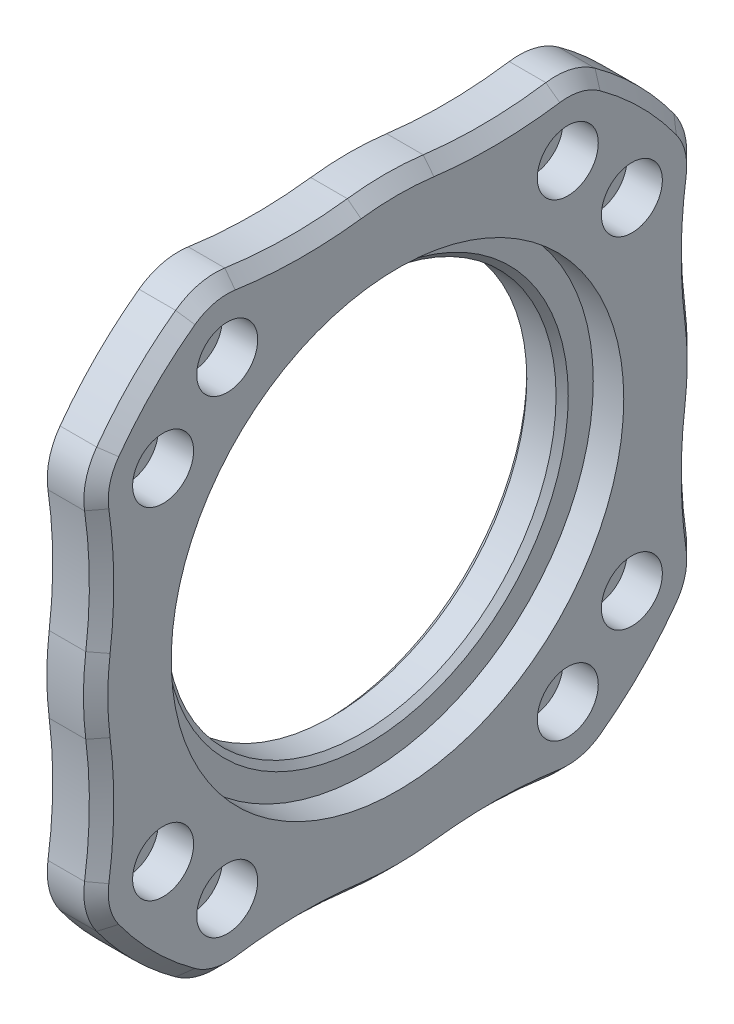
SolidWorks part; units mm, degrees
ref_plane "前视基准面" through (0, 0, 0) normal (1, 0, 0) x (0, 1, 0)
ref_plane "上视基准面" through (0, 0, 0) normal (0, 0, 1) x (0, 1, 0)
ref_plane "右视基准面" through (0, 0, 0) normal (0, 1, 0) x (-1, 0, 0)
other "Configuration Table"
sketch "草图1" plane through (0, 0, 0) normal (1, 0, 0) x (0, 1, 0)
  circle A0 centre (0, 0) radius 30
  dimension "D1" = 60
extrude "凸台-拉伸1" add sketch "草图1" along normal blind 4
sketch "草图2" plane through (0, 0, 0) normal (-1, 0, 0) x (0, -1, 0)
  line L0 (0, 30) -> (0, 0) construction
  line L1 (0, 0) -> (-30, 0) construction
  line L3 (-13.9599, -19.2142) -> (0, 0) construction
  line L4 (0, 0) -> (-21.2132, -21.2132) construction
  arc A0 (-15.4294, -21.2367) -> (-13.5954, -21.6874) centre (-13.9599, -19.2142) ccw
  arc A1 (-2.7345, -21.5774) -> (-13.5954, -21.6874) centre (-7.7635, -61.26) ccw
  arc A2 (-2.7345, -21.5774) -> (2.7345, -21.5774) centre (0, 0) ccw
  arc A3 (-21.2367, -15.4294) -> (-15.4294, -21.2367) centre (0, 0) ccw
  arc A4 (-21.2367, -15.4294) -> (-21.6874, -13.5954) centre (-19.2142, -13.9599) cw
  arc A5 (-21.5774, -2.7345) -> (-21.6874, -13.5954) centre (-61.26, -7.7635) cw
  arc A6 (-21.5774, -2.7345) -> (-21.5774, 2.7345) centre (0, 0) cw
  arc A7 (-21.5774, 2.7345) -> (-21.6874, 13.5954) centre (-61.26, 7.7635) ccw
  arc A8 (-21.2367, 15.4294) -> (-21.6874, 13.5954) centre (-19.2142, 13.9599) ccw
  arc A9 (-21.2367, 15.4294) -> (-15.4294, 21.2367) centre (0, 0) cw
  arc A10 (-15.4294, 21.2367) -> (-13.5954, 21.6874) centre (-13.9599, 19.2142) cw
  arc A11 (-2.7345, 21.5774) -> (-13.5954, 21.6874) centre (-7.7635, 61.26) cw
  arc A12 (-2.7345, 21.5774) -> (2.7345, 21.5774) centre (0, 0) cw
  arc A13 (15.4294, 21.2367) -> (13.5954, 21.6874) centre (13.9599, 19.2142) ccw
  arc A14 (2.7345, 21.5774) -> (13.5954, 21.6874) centre (7.7635, 61.26) ccw
  arc A15 (21.2367, 15.4294) -> (15.4294, 21.2367) centre (0, 0) ccw
  arc A16 (21.2367, 15.4294) -> (21.6874, 13.5954) centre (19.2142, 13.9599) cw
  arc A17 (21.5774, 2.7345) -> (21.6874, 13.5954) centre (61.26, 7.7635) cw
  arc A18 (21.5774, -2.7345) -> (21.5774, 2.7345) centre (0, 0) ccw
  arc A19 (21.5774, -2.7345) -> (21.6874, -13.5954) centre (61.26, -7.7635) ccw
  arc A20 (21.2367, -15.4294) -> (21.6874, -13.5954) centre (19.2142, -13.9599) ccw
  arc A21 (21.2367, -15.4294) -> (15.4294, -21.2367) centre (0, 0) cw
  arc A22 (15.4294, -21.2367) -> (13.5954, -21.6874) centre (13.9599, -19.2142) cw
  arc A23 (2.7345, -21.5774) -> (13.5954, -21.6874) centre (7.7635, -61.26) cw
  circle A24 centre (0, 0) radius 30 construction
  dimension "D1" = 2.5
  dimension "D4" = 40
  dimension "D5" = 26.25
  dimension "D6" = 21.75
  dimension "D2" = 54
  dimension "D3" = 45
extrude "凸台-拉伸2" add sketch "草图2" along normal blind 1.9
chamfer "倒角1" distance 1 angle 45 24 edges at (0, -18.5616, -18.5616) (0, -21.6419, -14.5566) (0, -14.5566, -21.6419) (0, -21.2621, -8.1687) (0, -8.1687, -21.2621) (0, -21.75, 0) (0, 0, -21.75) (0, -21.2621, 8.1687) (0, 8.1687, -21.2621) (0, -21.6419, 14.5566) (0, 14.5566, -21.6419) (0, -18.5616, 18.5616) (0, 18.5616, -18.5616) (0, -14.5566, 21.6419) (0, 21.6419, -14.5566) (0, -8.1687, 21.2621) (0, 21.2621, -8.1687) (0, 0, 21.75) (0, 21.75, 0) (0, 8.1687, 21.2621) (0, 21.2621, 8.1687) (0, 14.5566, 21.6419) (0, 21.6419, 14.5566) (0, 18.5616, 18.5616)
sketch "草图5" plane through (4, 0, 0) normal (1, 0, 0) x (0, 1, 0)
  circle A0 centre (0, 0) radius 16
  dimension "D1" = 32
extrude "切除-拉伸2" cut sketch "草图5" against normal through all
sketch "草图6" plane through (4, 0, 0) normal (1, 0, 0) x (0, 1, 0)
  line L0 (0, 0) -> (23.75, 0) construction
  line L1 (0, 0) -> (0, 23.75) construction
  line L2 (13.9599, 19.2142) -> (0, 0) construction
  line L3 (0, 0) -> (19.2142, 13.9599) construction
  circle A0 centre (0, 0) radius 23.75 construction
  point P4 (13.9599, 19.2142)
  point P6 (19.2142, 13.9599)
  point P12 (19.2142, -13.9599)
  point P13 (13.9599, -19.2142)
  point P14 (-13.9599, -19.2142)
  point P15 (-19.2142, -13.9599)
  point P16 (-19.2142, 13.9599)
  point P17 (-13.9599, 19.2142)
  dimension "D1" = 47.5
  dimension "D2" = 36
  dimension "D3" = 36
  dimension "D4" = 4
hole_wizard "M2.5 六角圆柱头螺钉的柱形沉头孔1" positions "草图6" profile "草图7" counterbore size "M2.5" standard "GB" end condition up to next
sketch "草图7" plane through (4, -13.9599, 19.2142) normal (0, 1, 0) x (0, 0, -1)
  line L0 (0, 0) -> (0, 5.9)
  line L1 (0, 5.9) -> (1.35, 5.9)
  line L3 (1.35, 5.9) -> (1.35, 2.9)
  line L4 (1.35, 2.9) -> (2.5, 2.9)
  line L5 (2.5, 2.9) -> (2.5, 0)
  line L7 (2.5, 0) -> (0, 0)
  line L11 (0, -6.35) -> (0, 107.95) construction
  dimension "通孔孔直径" = 2.7
  dimension "通孔孔深度" = 5.9
  dimension "柱形沉头孔直径" = 5
  dimension "柱形沉头孔深度" = 2.9
sketch "草图8" plane through (4, 0, 0) normal (1, 0, 0) x (0, 0, -1)
  line L0 (0, 30) -> (0, 0) construction
  line L1 (0, 0) -> (-30, 0) construction
  line L2 (-13.9599, -19.2142) -> (0, 0) construction
  line L3 (0, 0) -> (-31.7925, -31.7925) construction
  arc A0 (-15.4294, -21.2367) -> (-13.5954, -21.6874) centre (-13.9599, -19.2142) ccw construction
  arc A1 (-2.7345, -21.5774) -> (-13.5954, -21.6874) centre (-7.7635, -61.26) ccw construction
  arc A2 (-2.7345, -21.5774) -> (2.7345, -21.5774) centre (0, 0) ccw construction
  arc A3 (-21.2367, -15.4294) -> (-15.4294, -21.2367) centre (0, 0) ccw construction
  arc A4 (-21.2367, -15.4294) -> (-21.6874, -13.5954) centre (-19.2142, -13.9599) cw construction
  arc A5 (-21.5774, -2.7345) -> (-21.6874, -13.5954) centre (-61.26, -7.7635) cw construction
  arc A6 (-21.5774, -2.7345) -> (-21.5774, 2.7345) centre (0, 0) cw construction
  arc A7 (-21.5774, 2.7345) -> (-21.6874, 13.5954) centre (-61.26, 7.7635) ccw construction
  arc A8 (-21.2367, 15.4294) -> (-21.6874, 13.5954) centre (-19.2142, 13.9599) ccw construction
  arc A9 (-21.2367, 15.4294) -> (-15.4294, 21.2367) centre (0, 0) cw construction
  arc A10 (-15.4294, 21.2367) -> (-13.5954, 21.6874) centre (-13.9599, 19.2142) cw construction
  arc A11 (-2.7345, 21.5774) -> (-13.5954, 21.6874) centre (-7.7635, 61.26) cw construction
  arc A12 (-2.7345, 21.5774) -> (2.7345, 21.5774) centre (0, 0) cw construction
  arc A13 (15.4294, 21.2367) -> (13.5954, 21.6874) centre (13.9599, 19.2142) ccw construction
  arc A14 (2.7345, 21.5774) -> (13.5954, 21.6874) centre (7.7635, 61.26) ccw construction
  arc A15 (21.2367, 15.4294) -> (15.4294, 21.2367) centre (0, 0) ccw construction
  arc A16 (21.2367, 15.4294) -> (21.6874, 13.5954) centre (19.2142, 13.9599) cw construction
  arc A17 (21.5774, 2.7345) -> (21.6874, 13.5954) centre (61.26, 7.7635) cw construction
  arc A18 (21.5774, -2.7345) -> (21.5774, 2.7345) centre (0, 0) ccw construction
  arc A19 (21.5774, -2.7345) -> (21.6874, -13.5954) centre (61.26, -7.7635) ccw construction
  arc A20 (21.2367, -15.4294) -> (21.6874, -13.5954) centre (19.2142, -13.9599) ccw construction
  arc A21 (21.2367, -15.4294) -> (15.4294, -21.2367) centre (0, 0) cw construction
  arc A22 (15.4294, -21.2367) -> (13.5954, -21.6874) centre (13.9599, -19.2142) cw construction
  arc A23 (2.7345, -21.5774) -> (13.5954, -21.6874) centre (7.7635, -61.26) cw construction
  circle A24 centre (0, 0) radius 30 construction
  arc A25 (-3.1117, 24.5536) -> (-13.158, 24.6554) centre (-7.7635, 61.26) cw
  arc A26 (-17.1927, 23.6637) -> (-13.158, 24.6554) centre (-13.9599, 19.2142) cw
  arc A27 (-23.6637, 17.1927) -> (-17.1927, 23.6637) centre (0, 0) cw
  arc A28 (-23.6637, 17.1927) -> (-24.6554, 13.158) centre (-19.2142, 13.9599) ccw
  arc A29 (-24.5536, 3.1117) -> (-24.6554, 13.158) centre (-61.26, 7.7635) ccw
  arc A30 (-24.5536, -3.1117) -> (-24.5536, 3.1117) centre (0, 0) cw
  arc A31 (-24.5536, -3.1117) -> (-24.6554, -13.158) centre (-61.26, -7.7635) cw
  arc A32 (-23.6637, -17.1927) -> (-24.6554, -13.158) centre (-19.2142, -13.9599) cw
  arc A33 (-23.6637, -17.1927) -> (-17.1927, -23.6637) centre (0, 0) ccw
  arc A34 (-17.1927, -23.6637) -> (-13.158, -24.6554) centre (-13.9599, -19.2142) ccw
  arc A35 (-3.1117, -24.5536) -> (-13.158, -24.6554) centre (-7.7635, -61.26) ccw
  arc A36 (-3.1117, -24.5536) -> (3.1117, -24.5536) centre (0, 0) ccw
  arc A37 (3.1117, -24.5536) -> (13.158, -24.6554) centre (7.7635, -61.26) cw
  arc A38 (17.1927, -23.6637) -> (13.158, -24.6554) centre (13.9599, -19.2142) cw
  arc A39 (23.6637, -17.1927) -> (17.1927, -23.6637) centre (0, 0) cw
  arc A40 (23.6637, -17.1927) -> (24.6554, -13.158) centre (19.2142, -13.9599) ccw
  arc A41 (24.5536, -3.1117) -> (24.6554, -13.158) centre (61.26, -7.7635) ccw
  arc A42 (24.5536, -3.1117) -> (24.5536, 3.1117) centre (0, 0) ccw
  arc A43 (24.5536, 3.1117) -> (24.6554, 13.158) centre (61.26, 7.7635) cw
  arc A44 (23.6637, 17.1927) -> (24.6554, 13.158) centre (19.2142, 13.9599) cw
  arc A45 (23.6637, 17.1927) -> (17.1927, 23.6637) centre (0, 0) ccw
  arc A46 (17.1927, 23.6637) -> (13.158, 24.6554) centre (13.9599, 19.2142) ccw
  arc A47 (3.1117, 24.5536) -> (13.158, 24.6554) centre (7.7635, 61.26) ccw
  arc A48 (-3.1117, 24.5536) -> (3.1117, 24.5536) centre (0, 0) cw
  dimension "D1" = 2.5
  dimension "D4" = 40
  dimension "D5" = 26.25
  dimension "D6" = 21.75
  dimension "D2" = 54
  dimension "D3" = 45
  dimension "D7" = 3
extrude "切除-拉伸3" cut sketch "草图8" against normal through all flip side to cut
chamfer "倒角2" distance 1 angle 45 24 edges at (4, -20.6829, -20.6829) (4, -15.2726, -24.5552) (4, -24.5552, -15.2726) (4, -8.1383, -24.2619) (4, -24.2619, -8.1383) (4, 0, -24.75) (4, -24.75, 0) (4, 8.1383, -24.2619) (4, -24.2619, 8.1383) (4, 15.2726, -24.5552) (4, -24.5552, 15.2726) (4, 20.6829, -20.6829) (4, -20.6829, 20.6829) (4, 24.5552, -15.2726) (4, -15.2726, 24.5552) (4, 24.2619, -8.1383) (4, -8.1383, 24.2619) (4, 24.75, 0) (4, 0, 24.75) (4, 24.2619, 8.1383) (4, 8.1383, 24.2619) (4, 24.5552, 15.2726) (4, 15.2726, 24.5552) (4, 20.6829, 20.6829)
sketch "草图9" plane through (4, 0, 0) normal (1, 0, 0) x (0, 0, -1)
  circle A0 centre (0, 0) radius 18.55
  dimension "D1" = 37.1
extrude "切除-拉伸4" cut sketch "草图9" against normal blind 2.5
chamfer "倒角3" distance 0.5 angle 45 2 edges at (1.5, 0, -16) (-1.9, 0, -16)
